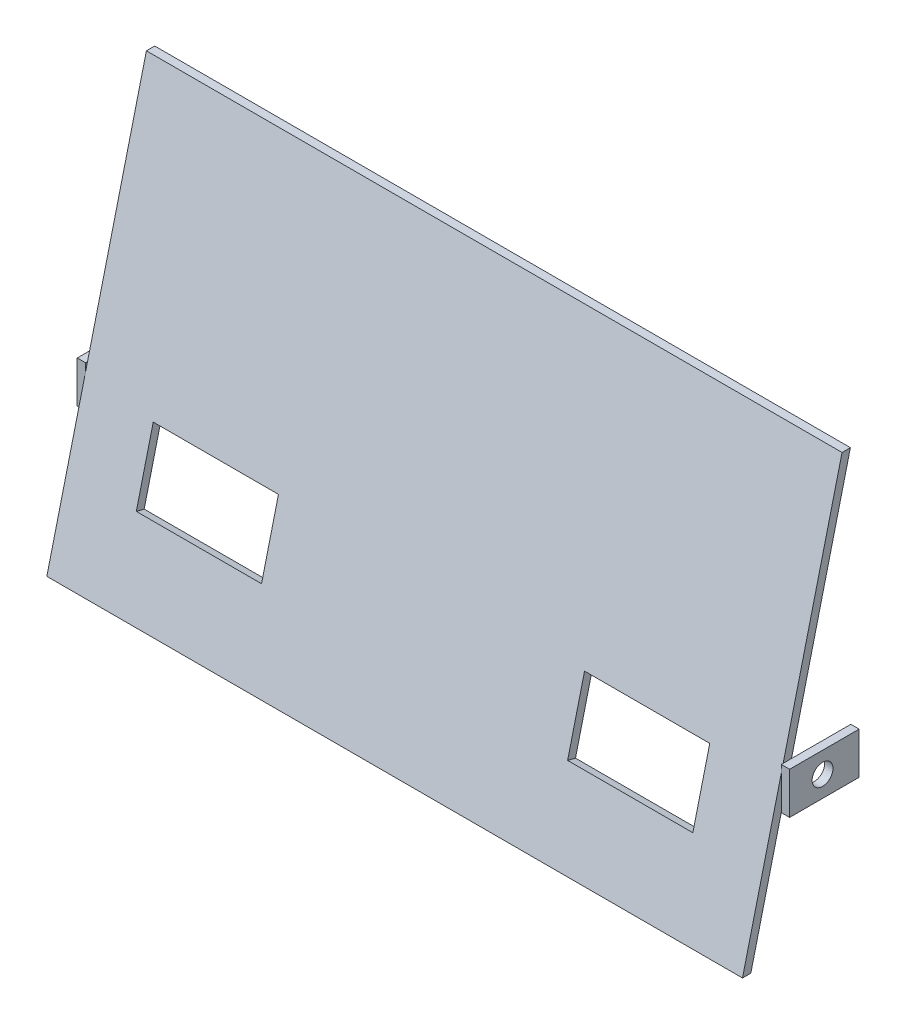
SolidWorks part; units mm, degrees
ref_plane "Alzado" through (0, 0, 0) normal (0, 0, 1) x (1, 0, 0)
ref_plane "Planta" through (0, 0, 0) normal (0, 1, 0) x (1, 0, 0)
ref_plane "Vista lateral" through (0, 0, 0) normal (1, 0, 0) x (0, 0, -1)
sketch "Croquis1" plane through (0, 0, 0) normal (1, 0, 0) x (0, 0, -1)
  line L0 (0, 0) -> (1.2, 0)
  line L1 (1.2, 0) -> (15.512, 58.2681)
  line L2 (0, 0) -> (14.312, 58.2681)
  line L3 (14.312, 58.2681) -> (15.512, 58.2681)
  line L4 (0, 0) -> (0, 2.8) construction
  line L5 (0, 2.8) -> (14.7473, 2.8) construction
  dimension "D1" = 1.2
  dimension "D2" = 60
  dimension "D3" = 13.8
  dimension "D4" = 2.8
extrude "Saliente-Extruir1" add sketch "Croquis1" against normal blind 100
sketch "Croquis3" plane through (0, 0, 0) normal (1, 0, 0) x (0, 0, -1)
  line L0 (0, 0) -> (0, 2.8) construction
  line L1 (0, 2.8) -> (11.5944, 2.8) construction
  line L2 (1.2, 0) -> (15.512, 58.2681) construction
  line L3 (5.5721, 17.8) -> (15.5721, 17.8)
  line L4 (5.5721, 17.8) -> (5.5721, 23.8)
  line L5 (5.5721, 23.8) -> (15.5721, 23.8)
  line L6 (15.5721, 17.8) -> (15.5721, 23.8)
  line L7 (5.5721, 17.8) -> (5.5721, 2.8) construction
  dimension "D1" = 2.8
  dimension "D2" = 6
  dimension "D3" = 10
  dimension "D4" = 15
extrude "Saliente-Extruir2" add sketch "Croquis3" along normal blind 1.2
sketch "Croquis4" plane through (-100, 0, 0) normal (-1, 0, 0) x (0, 0, 1)
  line L1 (-15.5721, 17.8) -> (-5.5721, 17.8)
  line L2 (-15.5721, 17.8) -> (-15.5721, 23.8)
  line L3 (-15.5721, 23.8) -> (-5.5721, 23.8)
  line L4 (-5.5721, 17.8) -> (-5.5721, 23.8)
extrude "Saliente-Extruir3" add sketch "Croquis4" along normal blind 1.2
sketch "Croquis5" plane through (1.2, 0, 0) normal (1, 0, 0) x (0, 0, -1)
  line L2 (5.5721, 20.8) -> (10.309, 20.8) construction
  line L3 (5.5721, 23.8) -> (5.5721, 17.8) construction
  line L4 (5.5721, 17.8) -> (7.0458, 23.8) construction
  circle A0 centre (10.309, 20.8) radius 1.5
  point P4 (6.309, 20.8)
  dimension "D2" = 3
  dimension "D1" = 4
extrude "Cortar-Extruir1" cut sketch "Croquis5" against normal through all
sketch "Croquis6" plane through (0, 0, 0) normal (0, 0.2385, 0.9711) x (1, 0, 0)
  line L0 (-50, 0) -> (-50, 61.0594) construction
  line L1 (-90, 22.2) -> (-72, 22.2)
  line L2 (-90, 22.2) -> (-90, 12)
  line L3 (-90, 12) -> (-72, 12)
  line L4 (-72, 22.2) -> (-72, 12)
  line L9 (-100, 0) -> (0, 0) construction
  line L10 (-100, 23.3598) -> (-100, 0) construction
  line L11 (-10, 12) -> (-28, 12)
  line L12 (-28, 22.2) -> (-28, 12)
  line L13 (-10, 22.2) -> (-28, 22.2)
  line L14 (-10, 22.2) -> (-10, 12)
  dimension "D1" = 18
  dimension "D2" = 10.2
  dimension "D3" = 10
  dimension "D4" = 12
extrude "Cortar-Extruir2" cut sketch "Croquis6" against normal blind 14
